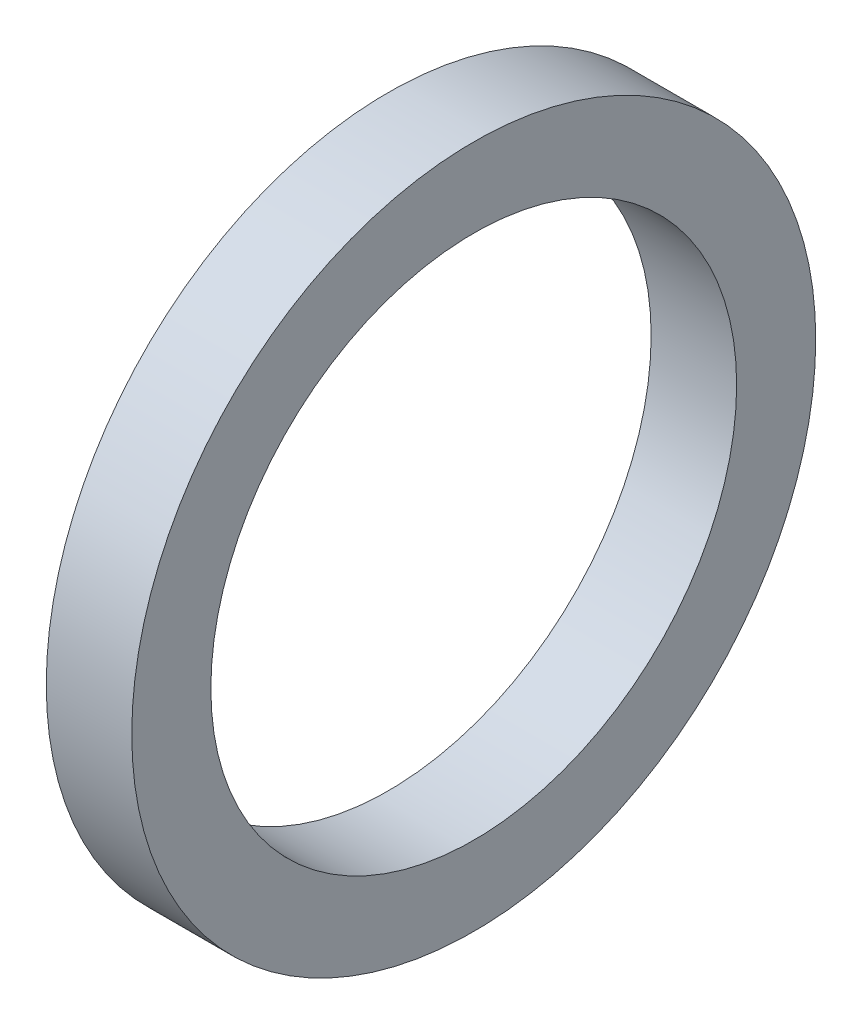
SolidWorks part; units mm, degrees
ref_plane "正面" through (0, 0, 0) normal (0, 0, 1) x (1, 0, 0)
ref_plane "平面" through (0, 0, 0) normal (0, 1, 0) x (1, 0, 0)
ref_plane "右側面" through (0, 0, 0) normal (1, 0, 0) x (0, 0, -1)
sketch "ｽｹｯﾁ1" plane through (0, 0, 0) normal (1, 0, 0) x (0, 0, -1)
  circle A0 centre (0, 0) radius 6.15
  circle A1 centre (0, 0) radius 8
  dimension "D1" = 12.3
  dimension "D2" = 16
extrude "ﾎﾞｽ - 押し出し1" add sketch "ｽｹｯﾁ1" along normal blind 2
equation "\"長さ\"= 2"
equation "\"D1@ﾎﾞｽ - 押し出し1\"=\"長さ\""
